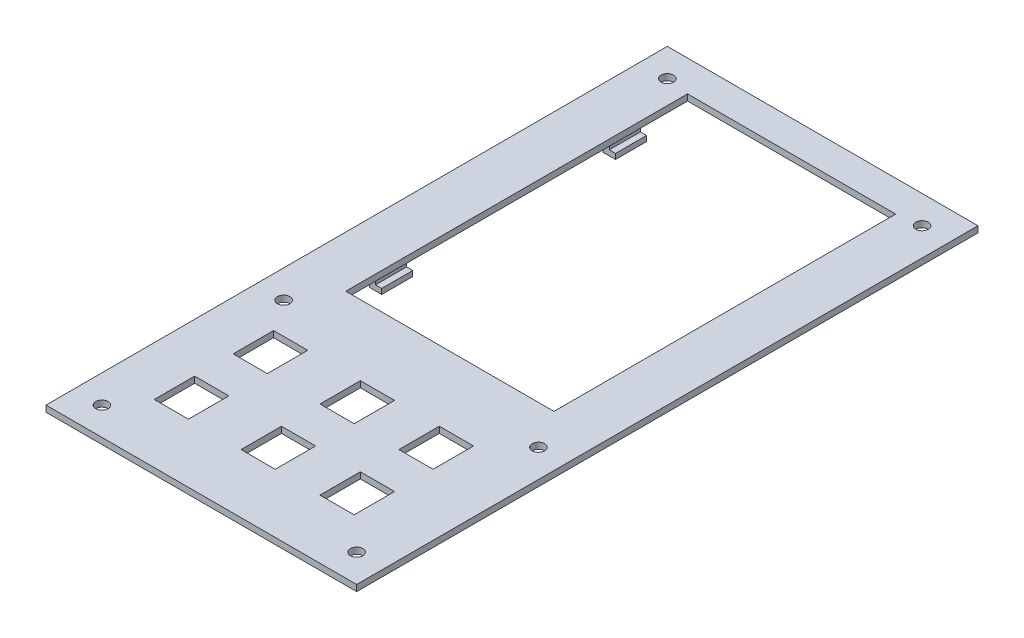
SolidWorks part; units mm, degrees
ref_plane "Front Plane" through (0, 0, 0) normal (0, 0, 1) x (1, 0, 0)
ref_plane "Top Plane" through (0, 0, 0) normal (0, 1, 0) x (1, 0, 0)
ref_plane "Right Plane" through (0, 0, 0) normal (1, 0, 0) x (0, 0, -1)
sketch "Sketch1" plane through (0, 0, 0) normal (0, 1, 0) x (1, 0, 0)
  line L1 (-50, 100) -> (50, 100)
  line L2 (-50, 100) -> (-50, -100)
  line L3 (-50, -100) -> (50, -100)
  line L4 (50, 100) -> (50, -100)
  line L5 (-50, 100) -> (50, -100) construction
  line L6 (-50, -100) -> (50, 100) construction
  line L7 (-33.5, 90) -> (33.5, 90)
  line L8 (-33.5, 90) -> (-33.5, -20)
  line L9 (-33.5, -20) -> (33.5, -20)
  line L10 (33.5, 90) -> (33.5, -20)
  line L11 (-33.5, 90) -> (33.5, -20) construction
  line L12 (-33.5, -20) -> (33.5, 90) construction
  point P0 (0, 0)
  dimension "D1" = 100
  dimension "D2" = 200
  dimension "D3" = 67
  dimension "D4" = 110
  dimension "D5" = 10
extrude "Boss-Extrude1" add sketch "Sketch1" along normal blind 2
sketch "Sketch2" plane through (0, 0, 0) normal (0, -1, 0) x (1, 0, 0)
  line L0 (-50, 100) -> (50, 100)
  line L1 (50, 100) -> (50, -100)
  line L2 (50, -100) -> (-50, -100)
  line L3 (-50, -100) -> (-50, 100)
  line L5 (-47, 97) -> (47, 97)
  line L6 (-47, 97) -> (-47, -97)
  line L7 (-47, -97) -> (47, -97)
  line L8 (47, 97) -> (47, -97)
  dimension "D1" = 3
  dimension "D2" = 3
  dimension "D3" = 3
  dimension "D4" = 3
extrude "Boss-Extrude2" add sketch "Sketch2" along normal blind 16.4
sketch "Sketch3" plane through (0, -16.4, 0) normal (0, -1, 0) x (1, 0, 0)
  line L0 (-50, 100) -> (50, 100)
  line L1 (50, -100) -> (50, 100) construction
  line L2 (50, 100) -> (-50, 100) construction
  line L3 (50, 100) -> (50, 10)
  line L4 (-50, 100) -> (-50, 10)
  line L5 (-50, 100) -> (-50, -100) construction
  line L6 (-35, 80) -> (35, 80)
  line L7 (35, 80) -> (35, 10)
  line L9 (-35, 80) -> (-35, 10)
  line L11 (-50, -9) -> (-30, -9)
  line L12 (50, -9) -> (50, 10)
  line L13 (-50, -9) -> (-50, 10)
  line L14 (-35, 10) -> (-35, 1)
  line L15 (35, 10) -> (35, 1)
  line L16 (35, 1) -> (30, 1)
  line L17 (-30, 1) -> (-30, -9)
  line L18 (30, 1) -> (30, -9)
  line L19 (-30, 1) -> (-35, 1)
  line L20 (30, -9) -> (50, -9)
  circle A0 centre (-35, 85) radius 1.15
  circle A1 centre (35, 85) radius 1.15
  circle A2 centre (-35, -4) radius 1.15
  circle A3 centre (35, -4) radius 1.15
  dimension "D1" = 2.3
  dimension "D2" = 2.3
  dimension "D12" = 2.3
  dimension "D15" = 2.3
  dimension "D3" = 15
  dimension "D4" = 15
  dimension "D5" = 15
  dimension "D6" = 15
  dimension "D7" = 15
  dimension "D8" = 15
  dimension "D9" = 20
  dimension "D10" = 5
  dimension "D11" = 5
  dimension "D13" = 0
  dimension "D14" = 89
  dimension "D16" = 70
  dimension "D17" = 5
  dimension "D18" = 5
extrude "Boss-Extrude3" add sketch "Sketch3" along normal blind 2
sketch "Sketch5" plane through (0, -16.4, 0) normal (0, -1, 0) x (1, 0, 0)
  line L0 (-50, -100) -> (50, -100)
  line L1 (50, -100) -> (50, -97)
  line L2 (50, -100) -> (50, -9) construction
  line L3 (47, -97) -> (-47, -97)
  line L4 (-50, -9) -> (-50, -100) construction
  line L5 (-50, -97) -> (-50, -100)
  line L6 (-50, -97) -> (-50, 10)
  line L7 (-50, 10) -> (-47, 10)
  line L8 (-47, -9) -> (-47, -97) construction
  line L9 (-47, 10) -> (-47, -97)
  line L10 (50, -97) -> (50, 10)
  line L11 (50, 10) -> (47, 10)
  line L12 (47, -97) -> (47, -9) construction
  line L13 (47, 10) -> (47, -97)
  dimension "D1" = 3
  dimension "D2" = 110
  dimension "D3" = 110
extrude "Boss-Extrude4" add sketch "Sketch5" along normal blind 25
sketch "Sketch8" plane through (0, -41.4, 0) normal (0, -1, 0) x (1, 0, 0)
  line L1 (-50, 10) -> (50, 10)
  line L2 (-50, 10) -> (-50, -100)
  line L3 (-50, -100) -> (50, -100)
  line L4 (50, 10) -> (50, -100)
extrude "Boss-Extrude5" add sketch "Sketch8" along normal blind 3
sketch "Sketch9" plane through (0, -16.4, 0) normal (0, 1, 0) x (1, 0, 0)
  line L0 (-35, 4) -> (-35, -85) construction
  line L2 (-34.15, -68) -> (-23.15, -68)
  line L3 (-34.15, -68) -> (-34.15, -81)
  line L4 (-34.15, -81) -> (-23.15, -81)
  line L5 (-23.15, -68) -> (-23.15, -81)
  line L6 (-34.15, -68) -> (-23.15, -81) construction
  line L7 (-34.15, -81) -> (-23.15, -68) construction
  line L8 (-6.21, -68) -> (4.79, -68)
  line L9 (-6.21, -68) -> (-6.21, -81)
  line L10 (-6.21, -81) -> (4.79, -81)
  line L11 (4.79, -68) -> (4.79, -81)
  line L12 (-6.21, -68) -> (4.79, -81) construction
  line L13 (-6.21, -81) -> (4.79, -68) construction
  line L14 (19.19, -68) -> (30.19, -68)
  line L15 (19.19, -68) -> (19.19, -81)
  line L16 (19.19, -81) -> (30.19, -81)
  line L17 (30.19, -68) -> (30.19, -81)
  line L18 (19.19, -68) -> (30.19, -81) construction
  line L19 (19.19, -81) -> (30.19, -68) construction
  line L20 (-34.15, -42.6) -> (-23.15, -42.6)
  line L21 (-34.15, -42.6) -> (-34.15, -55.6)
  line L22 (-34.15, -55.6) -> (-23.15, -55.6)
  line L23 (-23.15, -42.6) -> (-23.15, -55.6)
  line L24 (-34.15, -42.6) -> (-23.15, -55.6) construction
  line L25 (-34.15, -55.6) -> (-23.15, -42.6) construction
  line L26 (-6.21, -42.6) -> (4.79, -42.6)
  line L27 (-6.21, -42.6) -> (-6.21, -55.6)
  line L28 (-6.21, -55.6) -> (4.79, -55.6)
  line L29 (4.79, -42.6) -> (4.79, -55.6)
  line L30 (-6.21, -42.6) -> (4.79, -55.6) construction
  line L31 (-6.21, -55.6) -> (4.79, -42.6) construction
  line L32 (19.19, -42.6) -> (30.19, -42.6)
  line L33 (19.19, -42.6) -> (19.19, -55.6)
  line L34 (19.19, -55.6) -> (30.19, -55.6)
  line L35 (30.19, -42.6) -> (30.19, -55.6)
  line L36 (19.19, -42.6) -> (30.19, -55.6) construction
  line L37 (19.19, -55.6) -> (30.19, -42.6) construction
  point P4 (-28.65, -74.5)
  point P9 (-0.71, -74.5)
  point P14 (24.69, -74.5)
  point P19 (-28.65, -49.1)
  point P24 (-0.71, -49.1)
  point P29 (24.69, -49.1)
  dimension "D1" = 89
  dimension "D2" = 13
  dimension "D3" = 11
  dimension "D4" = 13
  dimension "D5" = 11
  dimension "D6" = 11
  dimension "D7" = 11
  dimension "D8" = 11
  dimension "D9" = 11
  dimension "D10" = 13
  dimension "D11" = 13
  dimension "D12" = 13
  dimension "D13" = 13
  dimension "D14" = 10.5
  dimension "D15" = 6.35
  dimension "D16" = 27.94
  dimension "D17" = 25.4
  dimension "D18" = 10.5
  dimension "D19" = 10.5
  dimension "D20" = 6.35
  dimension "D21" = 27.94
  dimension "D22" = 25.4
  dimension "D23" = 25.4
  dimension "D24" = 25.4
extrude "Cut-Extrude2" cut sketch "Sketch9" along normal blind 36
sketch "Sketch10" plane through (0, -44.4, 0) normal (0, -1, 0) x (1, 0, 0)
  line L0 (-50, 10) -> (-50, -100) construction
  line L1 (-43, 6.5) -> (-36, 6.5)
  line L2 (-43, 6.5) -> (-43, 3.5)
  line L3 (-43, 3.5) -> (-36, 3.5)
  line L4 (-36, 6.5) -> (-36, 3.5)
  line L5 (43, 6.5) -> (36, 6.5)
  line L6 (43, 6.5) -> (43, 3.5)
  line L7 (43, 3.5) -> (36, 3.5)
  line L8 (36, 6.5) -> (36, 3.5)
  line L10 (50, 10) -> (-50, 10) construction
  line L11 (50, -100) -> (50, 10) construction
  point P10 (-43, 5)
  point P18 (43, 5)
  dimension "D1" = 7
  dimension "D2" = 7
  dimension "D3" = 3
  dimension "D4" = 5
  dimension "D5" = 7
  dimension "D6" = 7
  dimension "D7" = 3
  dimension "D8" = 5
extrude "Cut-Extrude3" cut sketch "Sketch10" against normal blind 10
sketch "Sketch11" plane through (0, -18.4, 0) normal (0, -1, 0) x (1, 0, 0)
  line L0 (50, 100) -> (-50, 100) construction
  line L1 (-46.5, 95) -> (-43.5, 95)
  line L2 (-46.5, 95) -> (-46.5, 88)
  line L3 (-46.5, 88) -> (-43.5, 88)
  line L4 (-43.5, 95) -> (-43.5, 88)
  line L5 (43.5, 95) -> (46.5, 95)
  line L6 (43.5, 95) -> (43.5, 88)
  line L7 (43.5, 88) -> (46.5, 88)
  line L8 (46.5, 95) -> (46.5, 88)
  line L9 (-50, 100) -> (-50, 10) construction
  line L10 (50, 10) -> (50, 100) construction
  point P10 (-45, 95)
  point P13 (45, 95)
  dimension "D1" = 3
  dimension "D2" = 7
  dimension "D3" = 3
  dimension "D4" = 7
  dimension "D5" = 5
  dimension "D6" = 5
  dimension "D7" = 5
  dimension "D8" = 5
extrude "Cut-Extrude4" cut sketch "Sketch11" against normal blind 10
sketch "Sketch12" plane through (0, 0, 100) normal (0, 0, 1) x (1, 0, 0)
  line L0 (-50, -1) -> (50, -1)
  line L2 (-50, -1) -> (-50, -18.4)
  line L3 (-50, -18.4) -> (50, -18.4)
  line L4 (50, -1) -> (50, -18.4)
extrude "Cut-Extrude5" cut sketch "Sketch12" against normal blind 3
sketch "Sketch13" plane through (0, 0, 0) normal (0, -1, 0) x (1, 0, 0)
  line L1 (-61.7605, 107.6667) -> (84.477, 107.6667)
  line L2 (-61.7605, 107.6667) -> (-61.7605, -110.2697)
  line L3 (-61.7605, -110.2697) -> (84.477, -110.2697)
  line L4 (84.477, 107.6667) -> (84.477, -110.2697)
extrude "Cut-Extrude6" cut sketch "Sketch13" along normal blind 57
sketch "Sketch14" plane through (0, 2, 0) normal (0, 1, 0) x (1, 0, 0)
  line L0 (-50, -100) -> (50, -100) construction
  line L1 (-50, 100) -> (-50, -100) construction
  line L2 (50, -100) -> (50, 100) construction
  line L3 (50, 100) -> (-50, 100) construction
  circle A0 centre (-41, -91) radius 2
  circle A1 centre (41, -91) radius 2
  circle A2 centre (41, -32.5) radius 2
  circle A3 centre (-41, -32.5) radius 2
  circle A4 centre (-41, 91) radius 2
  circle A5 centre (41, 91) radius 2
  dimension "D2" = 9
  dimension "D3" = 9
  dimension "D4" = 9
  dimension "D5" = 9
  dimension "D6" = 9
  dimension "D7" = 9
  dimension "D8" = 9
  dimension "D9" = 9
  dimension "D10" = 9
  dimension "D11" = 58.5
  dimension "D12" = 58.5
  dimension "D13" = 4
  dimension "D14" = 4
  dimension "D15" = 4
  dimension "D16" = 4
  dimension "D17" = 4
  dimension "D18" = 4
  dimension "D1" = 9
extrude "Cut-Extrude7" cut sketch "Sketch14" against normal blind 57
sketch "Sketch15" plane through (0, 0, 0) normal (0, -1, 0) x (1, 0, 0)
  line L0 (-33.5, 20) -> (33.5, 20) construction
  line L1 (-37.8, 8.1475) -> (-35.8, 8.1475)
  line L2 (-37.8, 8.1475) -> (-37.8, -1.8525)
  line L3 (-37.8, -1.8525) -> (-35.8, -1.8525)
  line L4 (-35.8, 8.1475) -> (-35.8, -1.8525)
  line L5 (-35.8, -67.1225) -> (-37.8, -67.1225)
  line L6 (-35.8, -67.1225) -> (-35.8, -77.1225)
  line L7 (-35.8, -77.1225) -> (-37.8, -77.1225)
  line L8 (-37.8, -67.1225) -> (-37.8, -77.1225)
  line L9 (39.8, 10) -> (41.8, 10)
  line L10 (39.8, 10) -> (39.8, 0)
  line L11 (39.8, 0) -> (41.8, 0)
  line L12 (41.8, 10) -> (41.8, 0)
  line L13 (39.8, -67.1225) -> (41.8, -67.1225)
  line L14 (39.8, -67.1225) -> (39.8, -77.1225)
  line L15 (39.8, -77.1225) -> (41.8, -77.1225)
  line L16 (41.8, -67.1225) -> (41.8, -77.1225)
  line L17 (-6.1142, -95) -> (3.8858, -95)
  line L18 (-6.1142, -95) -> (-6.1142, -97)
  line L19 (-6.1142, -97) -> (3.8858, -97)
  line L20 (3.8858, -95) -> (3.8858, -97)
  line L21 (-6.1142, 28) -> (3.8858, 28)
  line L22 (-6.1142, 28) -> (-6.1142, 26)
  line L23 (-6.1142, 26) -> (3.8858, 26)
  line L24 (3.8858, 28) -> (3.8858, 26)
  line L25 (33.5, -90) -> (-33.5, -90) construction
  line L26 (-33.5, -90) -> (-33.5, 20) construction
  line L27 (33.5, 20) -> (33.5, -90) construction
  dimension "D1" = 10
  dimension "D2" = 10
  dimension "D3" = 10
  dimension "D4" = 10
  dimension "D5" = 10
  dimension "D6" = 10
  dimension "D7" = 2
  dimension "D8" = 2
  dimension "D9" = 2
  dimension "D10" = 2
  dimension "D11" = 2
  dimension "D12" = 2
  dimension "D13" = 6
  dimension "D14" = 5
  dimension "D15" = 2.3
  dimension "D16" = 2.3
  dimension "D17" = 6.3
  dimension "D18" = 6.3
extrude "Boss-Extrude6" add sketch "Sketch15" along normal blind 5
sketch "Sketch16" plane through (-35.8, 0, 0) normal (1, 0, 0) x (0, 0, -1)
  line L0 (1.8525, -5) -> (1.8525, 0) construction
  line L1 (-8.1475, -5) -> (1.8525, -5)
  line L2 (-8.1475, -5) -> (-8.1475, -3.3)
  line L3 (-8.1475, -3.3) -> (1.8525, -3.3)
  line L4 (1.8525, -5) -> (1.8525, -3.3)
  line L5 (77.1225, -5) -> (77.1225, 0) construction
  line L6 (77.1225, -3.3) -> (67.1225, -3.3)
  line L7 (77.1225, -3.3) -> (77.1225, -5)
  line L8 (77.1225, -5) -> (67.1225, -5)
  line L9 (67.1225, -3.3) -> (67.1225, -5)
  dimension "D1" = 1.7
  dimension "D2" = 1.7
extrude "Boss-Extrude7" add sketch "Sketch16" along normal blind 2
sketch "Sketch17" plane through (39.8, 0, 0) normal (-1, 0, 0) x (0, 0, 1)
  line L0 (0, -5) -> (0, 0) construction
  line L1 (10, -5) -> (0, -5)
  line L2 (10, -5) -> (10, -3.3)
  line L3 (10, -3.3) -> (0, -3.3)
  line L4 (0, -5) -> (0, -3.3)
  line L5 (-77.1225, -5) -> (-77.1225, 0) construction
  line L6 (-67.1225, -5) -> (-77.1225, -5)
  line L7 (-67.1225, -5) -> (-67.1225, -3.3)
  line L8 (-67.1225, -3.3) -> (-77.1225, -3.3)
  line L9 (-77.1225, -5) -> (-77.1225, -3.3)
  dimension "D1" = 1.7
  dimension "D2" = 1.7
extrude "Boss-Extrude8" add sketch "Sketch17" along normal blind 2
